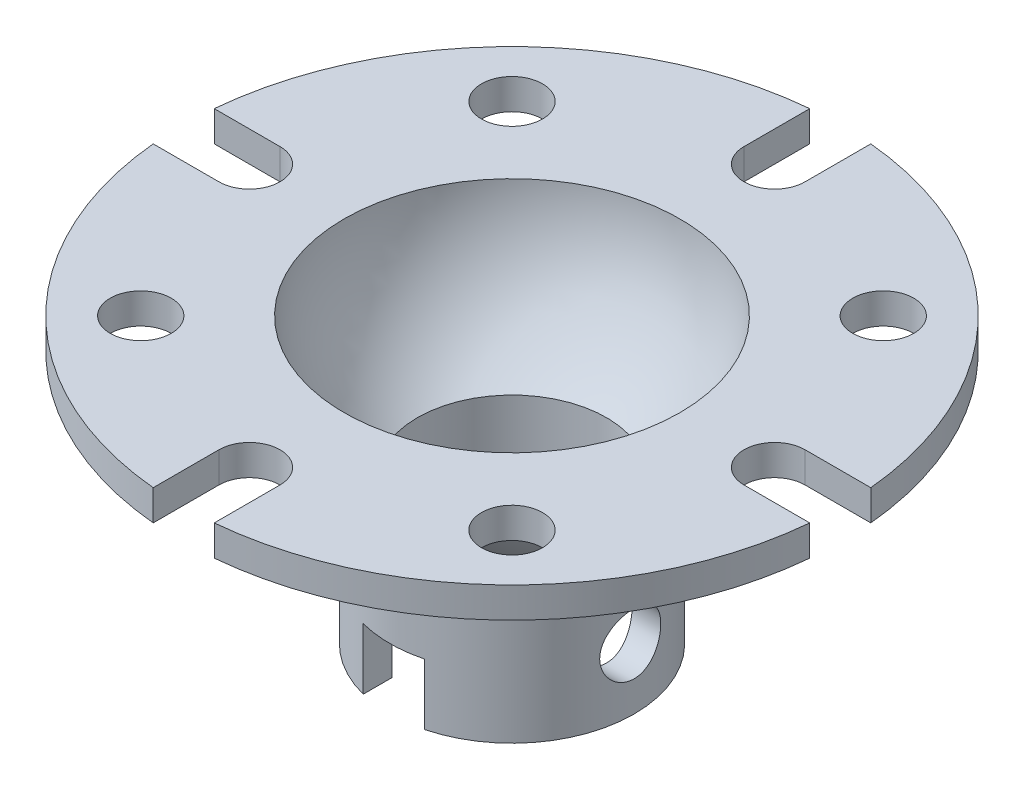
SolidWorks part; units mm, degrees
ref_plane "Piano frontale" through (0, 0, 0) normal (0, 0, 1) x (1, 0, 0)
ref_plane "Piano superiore" through (0, 0, 0) normal (0, 1, 0) x (1, 0, 0)
ref_plane "Piano destro" through (0, 0, 0) normal (1, 0, 0) x (0, 0, -1)
sketch "Schizzo1" plane through (0, 0, 0) normal (0, 0, 1) x (1, 0, 0)
  line L0 (0, 136.2489) -> (0, -136.2489) construction
  line L1 (31, 0) -> (40, 0)
  line L2 (40, 0) -> (40, 45)
  line L4 (63.6384, 83) -> (108, 83)
  line L5 (108, 83) -> (108, 93)
  line L6 (108, 93) -> (55, 93)
  line L8 (31, 48.6) -> (31, 0)
  arc A0 (40, 45) -> (63.6384, 83) centre (0, 96.2348) ccw
  arc A1 (31, 48.6) -> (55, 93) centre (-1.9612, 95.1033) ccw
  point P2 (0, 0)
  point P12 (0, 0)
  point P15 (0, 0)
  point P16 (0, 93.4235)
  point P17 (73.0206, 83)
  point P18 (0, 136.2489)
  point P19 (0, 0)
  point P20 (0, 0)
  dimension "D4" = 57
  dimension "D5" = 65
  dimension "D1" = 10
  dimension "D2" = 45
  dimension "D3" = 48.6
  dimension "D6" = 93
  dimension "D7" = 216
  dimension "D8" = 80
  dimension "D9" = 62
  dimension "D10" = 110
revolve "Rivoluzione1" add sketch "Schizzo1" angle 360 about L0
sketch "Schizzo2" plane through (0, 93, 0) normal (0, 1, 0) x (1, 0, 0)
  line L0 (0, 0) -> (60.8112, 60.8112) construction
  line L1 (0, 0) -> (86, 0) construction
  line L2 (107.536, 10) -> (86, 10)
  line L4 (107.536, -10) -> (86, -10)
  circle A0 centre (0, 0) radius 86 construction
  circle A1 centre (60.8112, 60.8112) radius 10
  arc A2 (86, 10) -> (86, -10) centre (86, 0) ccw
  arc A4 (107.536, -10) -> (107.536, 10) centre (0, 0) ccw
  circle A5 centre (0, 0) radius 108 construction
  point P12 (0, 0)
  dimension "D1" = 172
  dimension "D3" = 20
  dimension "D4" = 10
  dimension "D2" = 45
extrude "Taglio-Estrusione2" cut sketch "Schizzo2" against normal blind 10
pattern_circular "RipetizioneCircolare2" count 4 every 90 about axis through (0, 0, 0) along (0, 1, 0) of "Taglio-Estrusione2"
sketch "Schizzo4" plane through (0, 0, 0) normal (1, 0, 0) x (0, 0, -1)
  line L0 (0, 0) -> (0, 48.6) construction
  line L1 (-40, 0) -> (40, 0) construction
  circle A0 centre (0, 20) radius 10
  point P4 (0, 0)
  dimension "D1" = 20
  dimension "D2" = 20
extrude "Taglio-Estrusione3" cut sketch "Schizzo4" against normal up to next and the other way up to next
sketch "Schizzo5" plane through (0, 0, 0) normal (0, 0, 1) x (1, 0, 0)
  line L1 (-10, 20) -> (10, 20)
  line L2 (-10, 20) -> (-10, 0)
  line L3 (-10, 0) -> (10, 0)
  line L4 (10, 20) -> (10, 0)
  point P4 (0, 0)
  dimension "D1" = 20
  dimension "D2" = 20
extrude "Taglio-Estrusione4" cut sketch "Schizzo5" against normal up to next and the other way up to next
